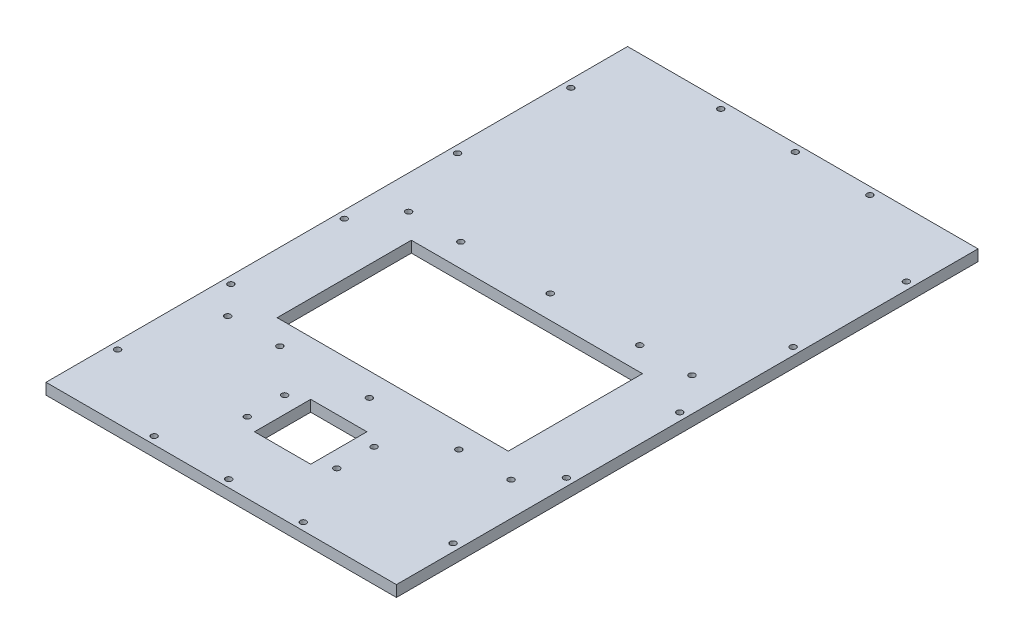
SolidWorks part; units mm, degrees
material "Acrylic (Medium-high impact)"
ref_plane "Front Plane" through (0, 0, 0) normal (0, 0, 1) x (1, 0, 0)
ref_plane "Top Plane" through (0, 0, 0) normal (0, 1, 0) x (1, 0, 0)
ref_plane "Right Plane" through (0, 0, 0) normal (1, 0, 0) x (0, 0, -1)
sketch "Sketch1" plane through (0, 0, 0) normal (0, 1, 0) x (1, 0, 0)
  line L1 (-149.225, -247.65) -> (149.225, -247.65)
  line L2 (-149.225, -247.65) -> (-149.225, 247.65)
  line L3 (-149.225, 247.65) -> (149.225, 247.65)
  line L4 (149.225, -247.65) -> (149.225, 247.65)
  line L5 (-149.225, -247.65) -> (149.225, 247.65) construction
  line L6 (-149.225, 247.65) -> (149.225, -247.65) construction
  line L7 (73.025, -247.65) -> (-130.175, -247.65)
  line L11 (-384.175, -247.65) -> (-231.775, -247.65)
  point P0 (0, 0)
  dimension "D1" = 298.45
  dimension "D2" = 495.3
extrude "Boss-Extrude1" add sketch "Sketch1" along normal mid plane 9.525 contours L1 L4 L3 L2
sketch "Sketch2" [suppressed] plane through (0, 0, 0) normal (0, 1, 0) x (1, 0, 0)
  line L0 (-250.825, -28.575) -> (250.825, -28.575) construction
  line L1 (161.925, -28.575) -> (60.325, -28.575)
  line L2 (161.925, -28.575) -> (161.925, -92.075)
  line L3 (161.925, -92.075) -> (60.325, -92.075)
  line L4 (60.325, -28.575) -> (60.325, -92.075)
  line L5 (0, -5.2388) -> (0, 5.2388) construction
  line L6 (-79.375, -28.575) -> (-168.275, -28.575)
  line L7 (-79.375, -28.575) -> (-79.375, -92.075)
  line L8 (-79.375, -92.075) -> (-168.275, -92.075)
  line L9 (-168.275, -28.575) -> (-168.275, -92.075)
  line L10 (250.825, -28.575) -> (250.825, 28.575) construction
  line L11 (-250.825, -28.575) -> (-250.825, 28.575) construction
  line L12 (-250.825, 28.575) -> (250.825, 28.575) construction
  line L13 (250.825, -28.575) -> (250.825, 28.575) construction
  line L14 (161.925, -28.575) -> (250.825, -28.575)
  line L15 (161.925, -28.575) -> (161.925, -71.755)
  line L16 (161.925, -71.755) -> (250.825, -71.755)
  line L17 (250.825, -28.575) -> (250.825, -71.755)
  line L18 (-250.825, -28.575) -> (-250.825, 28.575) construction
  line L19 (-79.375, -28.575) -> (60.325, -28.575)
  line L20 (-79.375, -28.575) -> (-79.375, -53.975)
  line L21 (-79.375, -53.975) -> (60.325, -53.975)
  line L22 (60.325, -28.575) -> (60.325, -53.975)
  line L23 (-168.275, -28.575) -> (-250.825, -28.575)
  line L24 (-168.275, -28.575) -> (-168.275, -71.755)
  line L25 (-168.275, -71.755) -> (-250.825, -71.755)
  line L26 (-250.825, -28.575) -> (-250.825, -71.755)
  point P19 (60.325, -92.075)
  dimension "D1" = 139.7
  dimension "D2" = 88.9
  dimension "D3" = 82.55
  dimension "D4" = 79.375
  dimension "D5" = 120.65
  dimension "D6" = 43.18
  dimension "D7" = 25.4
  dimension "D8" = 43.18
extrude "Boss-Extrude2" [suppressed] add sketch "Sketch2" along normal mid plane 9.525 contours L6 L9 L8 L7 | L23 L26 L25 L9 | L7 L21 L4 L19 | L17 L14 L2 L16
sketch "Sketch3" plane through (0, 4.7625, 0) normal (0, 1, 0) x (1, 0, 0)
  line L0 (-149.225, 247.65) -> (149.225, 247.65) construction
  line L1 (-98.425, 12.7) -> (98.425, 12.7)
  line L2 (-98.425, 12.7) -> (-98.425, -101.6)
  line L3 (-98.425, -101.6) -> (98.425, -101.6)
  line L4 (98.425, 12.7) -> (98.425, -101.6)
  line L5 (-98.425, 12.7) -> (98.425, -101.6) construction
  line L6 (-98.425, -101.6) -> (98.425, 12.7) construction
  line L7 (-149.225, -247.65) -> (149.225, -247.65) construction
  point P0 (0, -44.45)
  point P7 (0, 247.65)
  point P8 (0, 12.7)
  dimension "D1" = 196.85
  dimension "D2" = 114.3
  dimension "D3" = 203.2
extrude "Cut-Extrude1" cut sketch "Sketch3" against normal through all and the other way through all
sketch "Sketch4" [suppressed] plane through (0, -4.7625, 0) normal (0, -1, 0) x (1, 0, 0)
  line L0 (-107.315, 31.75) -> (107.315, 31.75) construction
  line L1 (-107.315, 33.9979) -> (107.315, 33.9979)
  line L2 (-107.315, 29.5021) -> (107.315, 29.5021)
  line L3 (-107.315, 6.35) -> (107.315, 6.35) construction
  line L4 (-107.315, 8.5979) -> (107.315, 8.5979)
  line L5 (-107.315, 4.1021) -> (107.315, 4.1021)
  arc A0 (-107.315, 33.9979) -> (-107.315, 29.5021) centre (-107.315, 31.75) ccw
  arc A1 (107.315, 29.5021) -> (107.315, 33.9979) centre (107.315, 31.75) ccw
  arc A2 (-107.315, 8.5979) -> (-107.315, 4.1021) centre (-107.315, 6.35) ccw
  arc A3 (107.315, 4.1021) -> (107.315, 8.5979) centre (107.315, 6.35) ccw
  point P0 (-107.315, 31.75)
  point P1 (107.315, 31.75)
  point P3 (107.315, 6.35)
  point P5 (-107.315, 6.35)
  point P10 (0, 31.75)
  point P15 (0, 6.35)
  dimension "D1" = 4.4958
  dimension "D2" = 4.4958
extrude "Cut-Extrude2" [suppressed] cut sketch "Sketch4" against normal through all
sketch "Sketch5" [suppressed] plane through (0, -4.7625, 0) normal (0, -1, 0) x (1, 0, 0)
  line L0 (69.85, 79.375) -> (69.85, -9.525) construction
  line L1 (60.325, 53.975) -> (60.325, 92.075) construction
  line L2 (161.925, 92.075) -> (60.325, 92.075) construction
  line L3 (-247.65, -22.225) -> (247.65, -22.225) construction
  line L4 (69.85, 79.375) -> (69.85, -9.525) construction
  line L5 (72.0979, 79.375) -> (72.0979, -9.525)
  line L6 (67.6021, 79.375) -> (67.6021, -9.525)
  line L7 (-88.9, 79.375) -> (-88.9, -9.525) construction
  line L8 (-79.375, 53.975) -> (-79.375, 92.075) construction
  line L9 (-79.375, 92.075) -> (-168.275, 92.075) construction
  line L10 (-88.9, 79.375) -> (-88.9, -9.525) construction
  line L11 (-86.6521, 79.375) -> (-86.6521, -9.525)
  line L12 (-91.1479, 79.375) -> (-91.1479, -9.525)
  arc A0 (72.0979, 79.375) -> (67.6021, 79.375) centre (69.85, 79.375) ccw
  arc A1 (67.6021, -9.525) -> (72.0979, -9.525) centre (69.85, -9.525) ccw
  arc A2 (-86.6521, 79.375) -> (-91.1479, 79.375) centre (-88.9, 79.375) ccw
  arc A3 (-91.1479, -9.525) -> (-86.6521, -9.525) centre (-88.9, -9.525) ccw
  point P8 (69.85, 34.925)
  point P19 (-88.9, 34.925)
  dimension "D1" = 9.525
  dimension "D2" = 12.7
  dimension "D3" = 12.7
  dimension "D4" = 4.4958
  dimension "D5" = 9.525
  dimension "D6" = 12.7
  dimension "D7" = 12.7
  dimension "D8" = 4.4958
extrude "Cut-Extrude3" [suppressed] cut sketch "Sketch5" against normal through all contours L12 A3 L11 A2 | L6 A1 L5 A0
sketch "Sketch6" [suppressed] plane through (0, 3.175, 0) normal (0, 1, 0) x (1, 0, 0)
  line L0 (-79.375, -38.1) -> (-79.375, 38.1) construction
  line L1 (-88.9, -50.8) -> (-88.9, 50.8) construction
  line L2 (-88.9, -50.8) -> (88.9, -50.8) construction
  line L3 (-88.9, 50.8) -> (88.9, 50.8) construction
  line L4 (79.375, -38.1) -> (79.375, 38.1) construction
  line L5 (88.9, -50.8) -> (88.9, 50.8) construction
  line L6 (-79.375, -38.1) -> (-79.375, 38.1) construction
  line L7 (-81.6229, -38.1) -> (-81.6229, 38.1)
  line L8 (-77.1271, -38.1) -> (-77.1271, 38.1)
  line L9 (79.375, -38.1) -> (79.375, 38.1) construction
  line L10 (77.1271, -38.1) -> (77.1271, 38.1)
  line L11 (81.6229, -38.1) -> (81.6229, 38.1)
  arc A0 (-81.6229, -38.1) -> (-77.1271, -38.1) centre (-79.375, -38.1) ccw
  arc A1 (-77.1271, 38.1) -> (-81.6229, 38.1) centre (-79.375, 38.1) ccw
  arc A2 (77.1271, -38.1) -> (81.6229, -38.1) centre (79.375, -38.1) ccw
  arc A3 (81.6229, 38.1) -> (77.1271, 38.1) centre (79.375, 38.1) ccw
  point P12 (-79.375, 0)
  point P17 (79.375, 0)
  dimension "D1" = 9.525
  dimension "D2" = 12.7
  dimension "D3" = 12.7
  dimension "D4" = 9.525
  dimension "D5" = 12.7
  dimension "D6" = 12.7
  dimension "D7" = 4.4958
  dimension "D8" = 4.4958
extrude "Cut-Extrude4" [suppressed] cut sketch "Sketch6" against normal through all
sketch "Sketch7" [suppressed] plane through (0, 4.7625, 0) normal (0, 1, 0) x (1, 0, 0)
  point P0 (115.1313, 66.802)
  point P1 (139.827, 42.1063)
  point P3 (-139.827, 42.1063)
  point P5 (-115.1313, 66.802)
hole_wizard "#12 Clearance Hole1" [suppressed] positions "Sketch8" profile "Sketch9" hole size "#12" standard "ANSI Inch"
sketch "Sketch8" plane through (0, 4.7625, 0) normal (0, 1, 0) x (1, 0, 0)
  point P0 (-139.827, 42.1063)
  point P3 (-115.1313, 66.802)
  point P6 (115.1313, 66.802)
  point P9 (139.827, 42.1063)
sketch "Sketch9" plane through (-139.827, 4.7625, -42.1063) normal (1, 0, 0) x (0, 0, 1)
  line L0 (0, 0) -> (0, 18.1964)
  line L1 (0, 18.1964) -> (2.8067, 16.51)
  line L2 (2.8067, 16.51) -> (2.8067, 0)
  line L5 (2.8067, 0) -> (0, 0)
  line L10 (0, 18.1964) -> (-2.8067, 16.51) construction
  line L11 (0, -6.35) -> (0, 107.95) construction
  dimension "Hole Dia." = 5.6134
  dimension "Hole Depth" = 16.51
  dimension "Drill Angle" = 118
sketch "Sketch10" [suppressed] plane through (0, -4.7625, 0) normal (0, -1, 0) x (1, 0, 0)
  point P0 (223.8375, -6.35)
  point P1 (223.8375, 19.05)
  point P3 (-223.8375, 19.05)
  point P5 (-223.8375, -6.35)
hole_wizard "#12 Clearance Hole3" [suppressed] positions "Sketch11" profile "Sketch12" hole size "#12" standard "ANSI Inch"
sketch "Sketch11" plane through (0, -4.7625, 0) normal (0, -1, 0) x (-1, 0, 0)
  point P0 (-223.8375, -19.05)
  point P3 (-223.8375, 6.35)
  point P6 (223.8375, -19.05)
  point P9 (223.8375, 6.35)
sketch "Sketch12" plane through (223.8375, -4.7625, 19.05) normal (1, 0, 0) x (0, 0, -1)
  line L0 (0, 0) -> (0, 18.1964)
  line L1 (0, 18.1964) -> (2.8067, 16.51)
  line L2 (2.8067, 16.51) -> (2.8067, 0)
  line L5 (2.8067, 0) -> (0, 0)
  line L10 (0, 18.1964) -> (-2.8067, 16.51) construction
  line L11 (0, -6.35) -> (0, 107.95) construction
  dimension "Hole Dia." = 5.6134
  dimension "Hole Depth" = 16.51
  dimension "Drill Angle" = 118
sketch "Sketch13" [suppressed] plane through (0, -4.7625, 0) normal (0, -1, 0) x (1, 0, 0)
  point P0 (133.35, -223.8375)
  point P1 (107.95, -223.8375)
  point P3 (-107.95, -223.8375)
  point P5 (-133.35, -223.8375)
  point P7 (133.35, 223.8375)
  point P9 (107.95, 223.8375)
  point P11 (-107.95, 223.8375)
  point P13 (-133.35, 223.8375)
hole_wizard "#12 Clearance Hole2" [suppressed] positions "Sketch14" profile "Sketch15" hole size "#12" standard "ANSI Inch"
sketch "Sketch14" [suppressed] plane through (0, -4.7625, 0) normal (0, -1, 0) x (-1, 0, 0)
  point P0 (107.95, -223.8375)
  point P3 (133.35, -223.8375)
  point P6 (133.35, 223.8375)
  point P9 (107.95, 223.8375)
  point P12 (-133.35, 223.8375)
  point P15 (-107.95, 223.8375)
  point P18 (-133.35, -223.8375)
  point P21 (-107.95, -223.8375)
sketch "Sketch15" plane through (-107.95, -4.7625, 223.8375) normal (1, 0, 0) x (0, 0, -1)
  line L0 (0, 0) -> (0, 18.1964)
  line L1 (0, 18.1964) -> (2.8067, 16.51)
  line L2 (2.8067, 16.51) -> (2.8067, 0)
  line L5 (2.8067, 0) -> (0, 0)
  line L10 (0, 18.1964) -> (-2.8067, 16.51) construction
  line L11 (0, -6.35) -> (0, 107.95) construction
  dimension "Hole Dia." = 5.6134
  dimension "Hole Depth" = 16.51
  dimension "Drill Angle" = 118
sketch "Sketch16" [suppressed] plane through (0, 3.175, 0) normal (0, 1, 0) x (1, 0, 0)
  line L0 (88.9, -50.8) -> (88.9, 50.8) construction
  line L1 (-88.9, -50.8) -> (-88.9, 50.8) construction
  line L2 (-88.9, -50.8) -> (88.9, -50.8) construction
  point P0 (79.375, -38.1)
  point P1 (-79.375, -38.1)
  dimension "D1" = 9.525
  dimension "D2" = 9.525
  dimension "D3" = 12.7
hole_wizard "#8 Clearance Hole1" [suppressed] positions "Sketch17" profile "Sketch19" hole size "#8" standard "ANSI Inch"
sketch "Sketch17" plane through (0, 3.175, 0) normal (0, 1, 0) x (1, 0, 0)
  point P0 (79.375, -38.1)
  point P3 (-79.375, -38.1)
sketch "Sketch19" plane through (79.375, 3.175, 38.1) normal (1, 0, 0) x (0, 0, 1)
  line L0 (0, 0) -> (0, 12.0187)
  line L1 (0, 12.0187) -> (2.2479, 10.668)
  line L2 (2.2479, 10.668) -> (2.2479, 0)
  line L5 (2.2479, 0) -> (0, 0)
  line L10 (0, 12.0187) -> (-2.2479, 10.668) construction
  line L11 (0, -6.35) -> (0, 107.95) construction
  dimension "Hole Dia." = 4.4958
  dimension "Hole Depth" = 10.668
  dimension "Drill Angle" = 118
sketch "Sketch20" plane through (0, -4.7625, 0) normal (0, -1, 0) x (1, 0, 0)
  line L0 (-149.225, 247.65) -> (149.225, 247.65) construction
  line L1 (23.9395, 147.5105) -> (-23.9395, 147.5105)
  line L2 (23.9395, 147.5105) -> (23.9395, 195.3895)
  line L3 (23.9395, 195.3895) -> (-23.9395, 195.3895)
  line L4 (-23.9395, 147.5105) -> (-23.9395, 195.3895)
  line L5 (23.9395, 147.5105) -> (-23.9395, 195.3895) construction
  line L6 (23.9395, 195.3895) -> (-23.9395, 147.5105) construction
  line L8 (38.1, 155.575) -> (-38.1, 155.575) construction
  line L9 (38.1, 155.575) -> (38.1, 187.325) construction
  line L10 (38.1, 187.325) -> (-38.1, 187.325) construction
  line L11 (-38.1, 155.575) -> (-38.1, 187.325) construction
  point P0 (0, 171.45)
  point P7 (0, 247.65)
  point P8 (38.1, 155.575)
  point P9 (38.1, 187.325)
  point P10 (-38.1, 155.575)
  point P11 (-38.1, 187.325)
  point P18 (0, 187.325)
  point P19 (0, 195.3895)
  point P20 (-38.1, 171.45)
  point P21 (-23.9395, 171.45)
  dimension "D1" = 47.879
  dimension "D2" = 47.879
  dimension "D3" = 38.1
  dimension "D4" = 15.875
  dimension "D5" = 76.2
extrude "Cut-Extrude5" cut sketch "Sketch20" against normal through all contours L1 L4 L3 L2
hole_wizard "#10 Clearance Hole1" positions "Sketch21" profile "Sketch22" hole size "#10" standard "ANSI Inch"
sketch "Sketch21" plane through (0, -4.7625, 0) normal (0, -1, 0) x (-1, 0, 0)
  point P0 (-38.1, -155.575)
  point P3 (38.1, -155.575)
  point P6 (38.1, -187.325)
  point P9 (-38.1, -187.325)
sketch "Sketch22" plane through (38.1, -4.7625, 155.575) normal (1, 0, 0) x (0, 0, -1)
  line L0 (0, 0) -> (0, 12.2018)
  line L1 (0, 12.2018) -> (2.5527, 10.668)
  line L2 (2.5527, 10.668) -> (2.5527, 0)
  line L5 (2.5527, 0) -> (0, 0)
  line L10 (0, 12.2018) -> (-2.5527, 10.668) construction
  line L11 (0, -6.35) -> (0, 107.95) construction
  dimension "Hole Dia." = 5.1054
  dimension "Hole Depth" = 10.668
  dimension "Drill Angle" = 118
sketch "Sketch23" [suppressed] plane through (-250.825, 0, 0) normal (-1, 0, 0) x (0, 0, 1)
  line L4 (-28.575, -4.7625) -> (71.755, -4.7625)
  line L5 (71.755, -4.7625) -> (71.755, 4.7625)
  line L6 (71.755, 4.7625) -> (-28.575, 4.7625)
  line L7 (-28.575, 4.7625) -> (-28.575, -4.7625)
  line L8 (-28.575, -4.7625) -> (71.755, -4.7625)
  line L9 (71.755, -4.7625) -> (71.755, 4.7625)
  line L10 (71.755, 4.7625) -> (-28.575, 4.7625)
  line L11 (-28.575, 4.7625) -> (-28.575, -4.7625)
  dimension "D1" = 0
extrude "Boss-Extrude3" [suppressed] add sketch "Sketch23" along normal blind 6.35
mirror "Mirror1" [suppressed] about plane through (0, 0, 0) normal (1, 0, 0)
sketch "Sketch27" [suppressed] plane through (0, 4.7625, 0) normal (0, 1, 0) x (1, 0, 0)
  line L1 (257.175, -71.755) -> (257.175, 28.575) construction
  line L2 (-257.175, 28.575) -> (257.175, 28.575) construction
  point P0 (241.3, 12.7)
  dimension "D1" = 15.875
  dimension "D2" = 15.875
hole_wizard "#10 Clearance Hole2" [suppressed] positions "Sketch28" profile "Sketch30" hole size "#10" standard "ANSI Inch"
sketch "Sketch28" plane through (0, 4.7625, 0) normal (0, 1, 0) x (1, 0, 0)
  point P0 (241.3, 12.7)
sketch "Sketch30" plane through (241.3, 4.7625, -12.7) normal (1, 0, 0) x (0, 0, 1)
  line L0 (0, 0) -> (0, 9.525)
  line L1 (0, 9.525) -> (2.5527, 9.525)
  line L2 (2.5527, 9.525) -> (2.5527, 0)
  line L5 (2.5527, 0) -> (0, 0)
  line L11 (0, -6.35) -> (0, 107.95) construction
  dimension "Thru Hole Dia." = 5.1054
  dimension "Thru Hole Depth" = 9.525
pattern_linear "LPattern1" [suppressed] count 6 spacing 96.52
sketch "Sketch31" [suppressed] plane through (0, 4.7625, 0) normal (0, 1, 0) x (1, 0, 0)
  line L1 (0, -5.2388) -> (0, 5.2388) construction
  line L2 (-149.225, 76.2) -> (149.225, 76.2) construction
  point P0 (-95.25, 60.325)
  dimension "D1" = 15.875
  dimension "D2" = 95.25
hole_wizard "#10 Clearance Hole3" [suppressed] positions "Sketch32" profile "Sketch33" hole size "#10" standard "ANSI Inch"
sketch "Sketch32" plane through (0, 4.7625, 0) normal (0, 1, 0) x (1, 0, 0)
  point P0 (-95.25, 60.325)
sketch "Sketch33" plane through (-95.25, 4.7625, -60.325) normal (1, 0, 0) x (0, 0, 1)
  line L0 (0, 0) -> (0, 9.525)
  line L1 (0, 9.525) -> (2.5527, 9.525)
  line L2 (2.5527, 9.525) -> (2.5527, 0)
  line L5 (2.5527, 0) -> (0, 0)
  line L11 (0, -6.35) -> (0, 107.95) construction
  dimension "Thru Hole Dia." = 5.1054
  dimension "Thru Hole Depth" = 9.525
pattern_linear "LPattern2" [suppressed] count 4 spacing 63.5
sketch "Sketch34" plane through (0, 4.7625, 0) normal (0, 1, 0) x (1, 0, 0)
  line L0 (0, -5.2388) -> (0, 5.2388) construction
  line L1 (-149.225, 247.65) -> (149.225, 247.65) construction
  point P0 (-63.5, 241.3)
  dimension "D1" = 63.5
  dimension "D2" = 6.35
hole_wizard "#10 Clearance Hole4" positions "Sketch35" profile "Sketch36" hole size "#10" standard "ANSI Inch" end condition up to next
sketch "Sketch35" plane through (0, 4.7625, 0) normal (0, 1, 0) x (1, 0, 0)
  point P0 (-63.5, 241.3)
sketch "Sketch36" plane through (-63.5, 4.7625, -241.3) normal (1, 0, 0) x (0, 0, 1)
  line L0 (0, 0) -> (0, 9.525)
  line L1 (0, 9.525) -> (2.5527, 9.525)
  line L2 (2.5527, 9.525) -> (2.5527, 0)
  line L5 (2.5527, 0) -> (0, 0)
  line L11 (0, -6.35) -> (0, 107.95) construction
  dimension "Thru Hole Dia." = 5.1054
  dimension "Thru Hole Depth" = 9.525
pattern_linear "LPattern3" count 3 spacing 63.5 along (1, 0, 0) of "#10 Clearance Hole4"
mirror "Mirror2" about plane through (0, 0, 0) normal (0, 0, 1) of "LPattern3", "#10 Clearance Hole4"
sketch "Sketch37" plane through (0, 4.7625, 0) normal (0, 1, 0) x (1, 0, 0)
  line L0 (-5.2388, 0) -> (5.2388, 0) construction
  line L1 (-149.225, -247.65) -> (-149.225, 247.65) construction
  point P0 (-142.875, 0)
  dimension "D1" = 6.35
hole_wizard "#10 Clearance Hole5" positions "Sketch38" profile "Sketch39" hole size "#10" standard "ANSI Inch" end condition up to next
sketch "Sketch38" plane through (0, 4.7625, 0) normal (0, 1, 0) x (1, 0, 0)
  point P0 (-142.875, 0)
sketch "Sketch39" plane through (-142.875, 4.7625, 0) normal (1, 0, 0) x (0, 0, 1)
  line L0 (0, 0) -> (0, 9.525)
  line L1 (0, 9.525) -> (2.5527, 9.525)
  line L2 (2.5527, 9.525) -> (2.5527, 0)
  line L5 (2.5527, 0) -> (0, 0)
  line L11 (0, -6.35) -> (0, 107.95) construction
  dimension "Thru Hole Dia." = 5.1054
  dimension "Thru Hole Depth" = 9.525
pattern_linear "LPattern4" count 3 spacing 96.52 along (0, 0, -1) count 3 spacing 96.52 along (0, 0, 1) of "#10 Clearance Hole5"
mirror "Mirror3" about plane through (0, 0, 0) normal (1, 0, 0) of "LPattern4", "#10 Clearance Hole5"
sketch "Sketch40" [suppressed] plane through (0, 4.7625, 0) normal (0, 1, 0) x (1, 0, 0)
  line L0 (-79.375, -53.975) -> (-79.375, -92.075) construction
  line L3 (-88.9, -79.375) -> (-88.9, -9.525) construction
  line L4 (-91.1479, -79.375) -> (-91.1479, -9.525)
  line L5 (-86.6521, -79.375) -> (-86.6521, -9.525)
  line L6 (69.85, -79.375) -> (69.85, -9.525) construction
  line L7 (67.6021, -79.375) -> (67.6021, -9.525)
  line L8 (72.0979, -79.375) -> (72.0979, -9.525)
  line L9 (60.325, -53.975) -> (60.325, -92.075) construction
  line L12 (-79.375, -92.075) -> (-168.275, -92.075) construction
  line L13 (161.925, -92.075) -> (60.325, -92.075) construction
  arc A2 (-91.1479, -79.375) -> (-86.6521, -79.375) centre (-88.9, -79.375) ccw
  arc A3 (-86.6521, -9.525) -> (-91.1479, -9.525) centre (-88.9, -9.525) ccw
  arc A4 (67.6021, -79.375) -> (72.0979, -79.375) centre (69.85, -79.375) ccw
  arc A5 (72.0979, -9.525) -> (67.6021, -9.525) centre (69.85, -9.525) ccw
  point P7 (-88.9, -44.45)
  point P14 (69.85, -44.45)
  dimension "D1" = 9.525
  dimension "D2" = 4.4958
  dimension "D3" = 4.4958
  dimension "D4" = 9.525
  dimension "D5" = 12.7
  dimension "D6" = 12.7
  dimension "D7" = 69.85
  dimension "D8" = 69.85
extrude "Cut-Extrude6" [suppressed] cut sketch "Sketch40" against normal up to next
sketch "Sketch41" plane through (0, -4.7625, 0) normal (0, -1, 0) x (1, 0, 0)
  point P0 (120.65, -32.5755)
  point P1 (-120.65, -32.5755)
  point P3 (-120.65, 121.4755)
  point P5 (120.65, 121.4755)
hole_wizard "#10 Clearance Hole6" positions "Sketch42" profile "Sketch43" hole size "#10" standard "ANSI Inch" end condition through all
sketch "Sketch42" plane through (0, 4.7625, 0) normal (0, 1, 0) x (1, 0, 0)
  point P0 (120.65, 32.5755)
  point P3 (120.65, -121.4755)
  point P6 (-120.65, -121.4755)
  point P9 (-120.65, 32.5755)
sketch "Sketch43" plane through (120.65, 4.7625, -32.5755) normal (1, 0, 0) x (0, 0, 1)
  line L0 (0, 0) -> (0, 9.525)
  line L1 (0, 9.525) -> (2.5527, 9.525)
  line L2 (2.5527, 9.525) -> (2.5527, 0)
  line L5 (2.5527, 0) -> (0, 0)
  line L11 (0, -6.35) -> (0, 107.95) construction
  dimension "Thru Hole Dia." = 5.1054
  dimension "Thru Hole Depth" = 9.525
sketch "Sketch44" plane through (0, 4.7625, 0) normal (0, 1, 0) x (1, 0, 0)
  line L0 (0, -5.2388) -> (0, 5.2388) construction
  line L2 (120.65, 32.5755) -> (-120.65, 32.5755) construction
  line L3 (120.65, -121.4755) -> (-120.65, -121.4755) construction
  point P0 (76.2, 32.5755)
  point P1 (0, 32.5755)
  point P2 (-76.2, 32.5755)
  point P3 (76.2, -121.4755)
  point P4 (0, -121.4755)
  point P5 (-76.2, -121.4755)
  point P10 (0, 0)
  point P11 (0, 0)
  dimension "D1" = 76.2
  dimension "D2" = 76.2
hole_wizard "#10 Clearance Hole7" positions "Sketch45" profile "Sketch46" hole size "#10" standard "ANSI Inch" end condition through all
sketch "Sketch45" plane through (0, 4.7625, 0) normal (0, 1, 0) x (1, 0, 0)
  point P0 (76.2, 32.5755)
  point P3 (0, 32.5755)
  point P6 (-76.2, 32.5755)
  point P9 (76.2, -121.4755)
  point P12 (0, -121.4755)
  point P15 (-76.2, -121.4755)
sketch "Sketch46" plane through (76.2, 4.7625, -32.5755) normal (1, 0, 0) x (0, 0, 1)
  line L0 (0, 0) -> (0, 9.525)
  line L1 (0, 9.525) -> (2.5527, 9.525)
  line L2 (2.5527, 9.525) -> (2.5527, 0)
  line L5 (2.5527, 0) -> (0, 0)
  line L11 (0, -6.35) -> (0, 107.95) construction
  dimension "Thru Hole Dia." = 5.1054
  dimension "Thru Hole Depth" = 9.525
